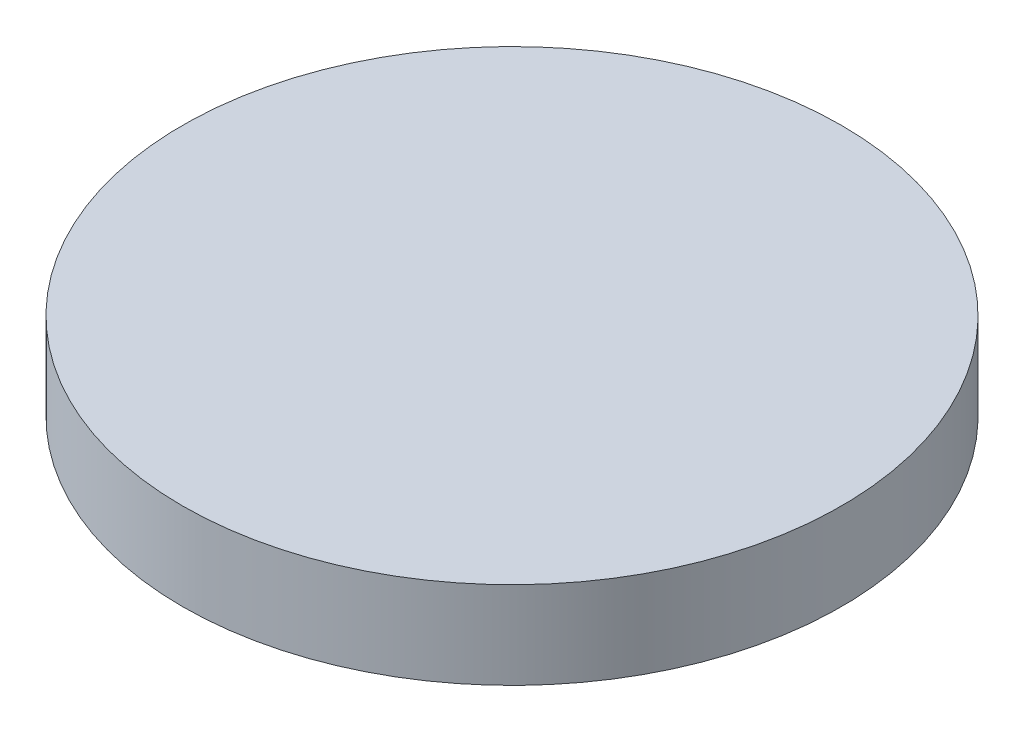
SolidWorks part; units mm, degrees
ref_plane "Front Plane" through (0, 0, 0) normal (0, 0, 1) x (1, 0, 0)
ref_plane "Top Plane" through (0, 0, 0) normal (0, 1, 0) x (1, 0, 0)
ref_plane "Right Plane" through (0, 0, 0) normal (1, 0, 0) x (0, 0, -1)
sketch "Sketch1" plane through (0, 0, 0) normal (0, 1, 0) x (1, 0, 0)
  circle A0 centre (0.9088, 0) radius 37.7773
extrude "Boss-Extrude1" add sketch "Sketch1" along normal blind 10
